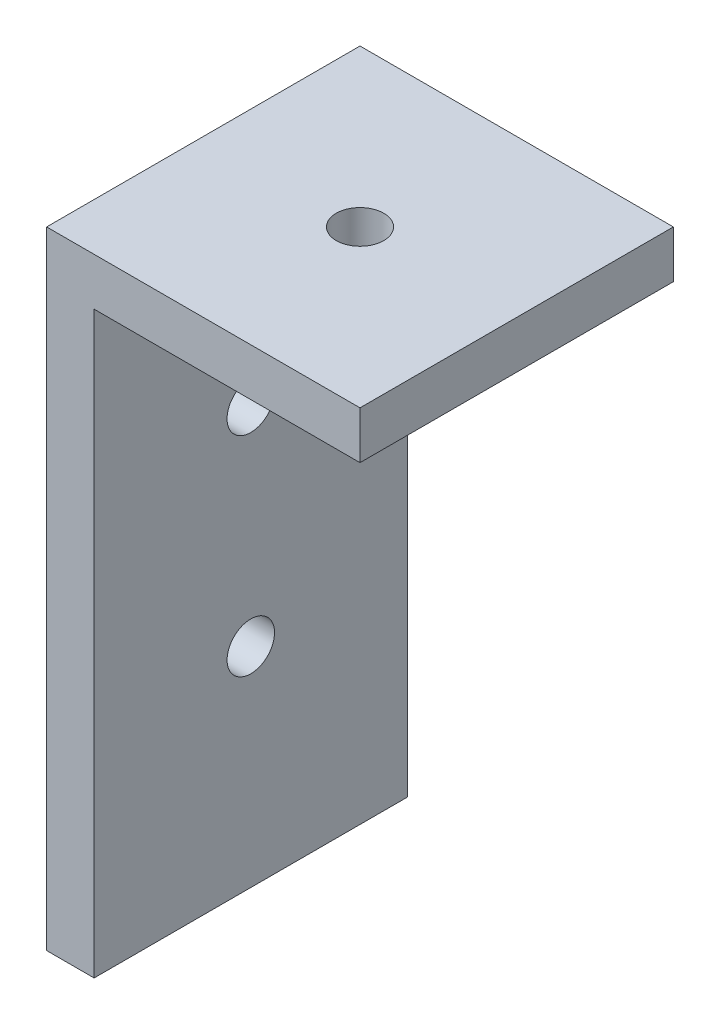
SolidWorks part; units mm, degrees
ref_plane "Front Plane" through (0, 0, 0) normal (0, 0, 1) x (1, 0, 0)
ref_plane "Top Plane" through (0, 0, 0) normal (0, 1, 0) x (1, 0, 0)
ref_plane "Right Plane" through (0, 0, 0) normal (1, 0, 0) x (0, 0, -1)
sketch "Sketch1" plane through (0, 0, 0) normal (0, 0, 1) x (1, 0, 0)
  line L0 (0, 0) -> (0, 36.6)
  line L1 (0, 36.6) -> (16.8, 36.6)
  line L2 (16.8, 36.6) -> (16.8, 39.6)
  line L3 (16.8, 39.6) -> (-3, 39.6)
  line L4 (-3, 39.6) -> (-3, 0)
  line L5 (-3, 0) -> (0, 0)
  dimension "D1" = 3
  dimension "D2" = 3
  dimension "D3" = 39.6
  dimension "D4" = 19.8
extrude "Boss-Extrude1" add sketch "Sketch1" along normal blind 19.8
sketch "Sketch2" plane through (0, 39.6, 0) normal (0, 1, 0) x (1, 0, 0)
  line L0 (16.8, -9.9) -> (-3, -9.9) construction
  line L1 (16.8, -19.8) -> (16.8, 0) construction
  line L2 (-3, -19.8) -> (-3, 0) construction
  circle A0 centre (6.9, -9.9) radius 1.5
  point P8 (6.9, -9.9)
  dimension "D1" = 3
extrude "Cut-Extrude1" cut sketch "Sketch2" against normal blind 19.8
sketch "Sketch3" plane through (-3, 0, 0) normal (-1, 0, 0) x (0, 0, 1)
  line L0 (19.8, 0) -> (0, 0) construction
  line L1 (9.9, 39.6) -> (9.9, 0) construction
  line L2 (19.8, 39.6) -> (0, 39.6) construction
  line L3 (0, 26.4) -> (19.8, 26.4) construction
  line L4 (0, 39.6) -> (0, 0) construction
  line L5 (19.8, 39.6) -> (19.8, 0) construction
  line L6 (0, 13.2) -> (19.8, 13.2) construction
  line L7 (15.8535, 39.6) -> (15.8535, 26.4) construction
  line L8 (15.8535, 26.4) -> (15.8535, 13.2) construction
  line L9 (15.8535, 13.2) -> (15.8535, 0) construction
  circle A0 centre (9.9, 26.4) radius 1.5
  circle A1 centre (9.9, 13.2) radius 1.5
  point P5 (9.9, 26.4)
  point P7 (9.9, 19.8)
  dimension "D1" = 3
extrude "Cut-Extrude2" cut sketch "Sketch3" against normal blind 19.8
